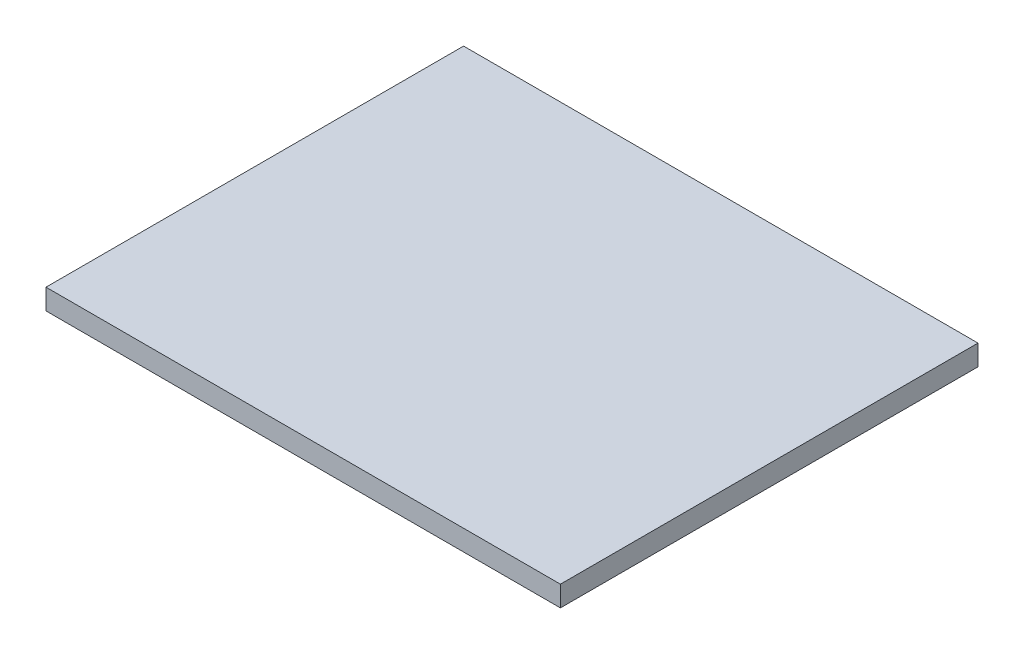
SolidWorks part; units mm, degrees
ref_plane "Front Plane" through (0, 0, 0) normal (0, 0, 1) x (1, 0, 0)
ref_plane "Top Plane" through (0, 0, 0) normal (0, 1, 0) x (1, 0, 0)
ref_plane "Right Plane" through (0, 0, 0) normal (1, 0, 0) x (0, 0, -1)
sketch "Sketch1" plane through (0, 0, 0) normal (0, 1, 0) x (1, 0, 0)
  line L1 (-212.5, 172.5) -> (212.5, 172.5)
  line L2 (-212.5, 172.5) -> (-212.5, -172.5)
  line L3 (-212.5, -172.5) -> (212.5, -172.5)
  line L4 (212.5, 172.5) -> (212.5, -172.5)
  line L5 (-212.5, 172.5) -> (212.5, -172.5) construction
  line L6 (-212.5, -172.5) -> (212.5, 172.5) construction
  point P0 (0, 0)
  dimension "D1" = 345
  dimension "D2" = 425
extrude "Boss-Extrude1" add sketch "Sketch1" along normal blind 17
